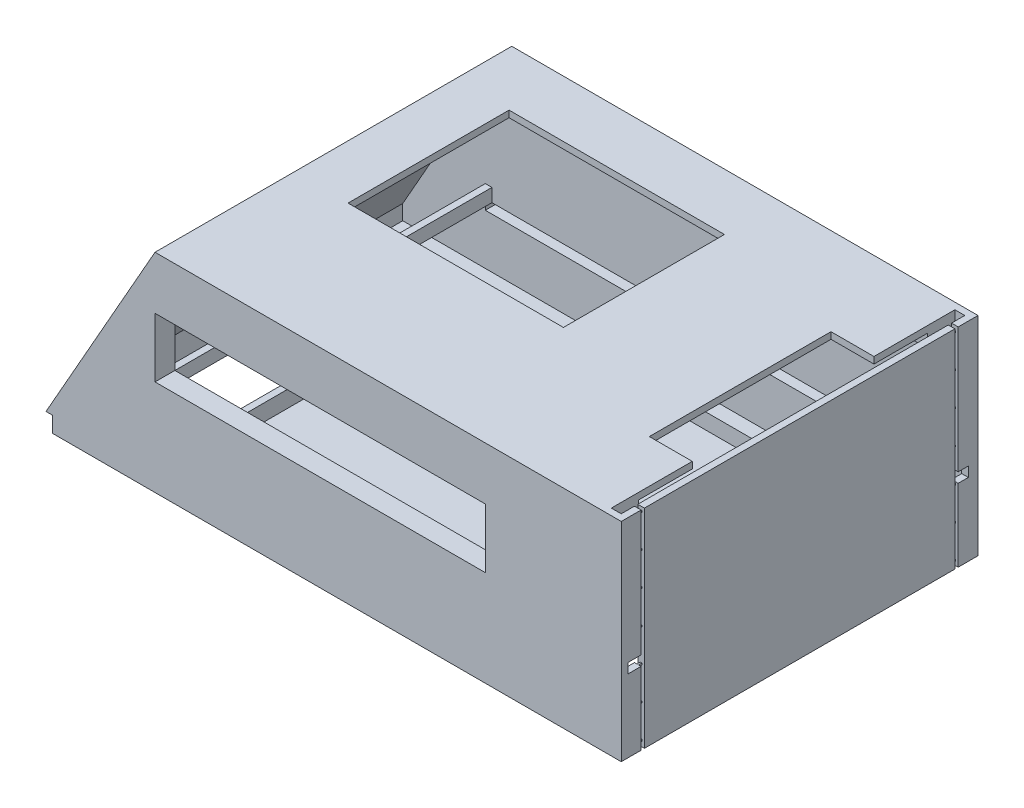
SolidWorks part; units mm, degrees
ref_plane "정면" through (0, 0, 0) normal (0, 0, 1) x (1, 0, 0)
ref_plane "윗면" through (0, 0, 0) normal (0, 1, 0) x (1, 0, 0)
ref_plane "우측면" through (0, 0, 0) normal (1, 0, 0) x (0, 0, -1)
sketch "스케치1" plane through (0, 0, 0) normal (0, 1, 0) x (1, 0, 0)
  line L1 (-87.075, 54) -> (87.075, 54)
  line L2 (-87.075, 54) -> (-87.075, -54)
  line L3 (-87.075, -54) -> (87.075, -54)
  line L4 (87.075, 54) -> (87.075, -54)
  line L5 (-87.075, 54) -> (87.075, -54) construction
  line L6 (-87.075, -54) -> (87.075, 54) construction
  point P0 (0, 0)
  dimension "D1" = 174.15
  dimension "D2" = 108
extrude "보스-돌출1" add sketch "스케치1" along normal blind 63
sketch "스케치4" plane through (87.075, 0, 0) normal (1, 0, 0) x (0, 0, -1)
  line L0 (-50, 0) -> (-50, 3)
  line L1 (-54, 0) -> (54, 0) construction
  line L2 (-50, 3) -> (-52, 3)
  line L3 (-52, 3) -> (-52, 4.5)
  line L4 (-52, 4.5) -> (-46, 4.5)
  line L5 (-46, 4.5) -> (-46, 3)
  line L6 (-46, 3) -> (-48, 3)
  line L7 (-48, 3) -> (-48, 0)
  line L8 (-48, 0) -> (-50, 0)
  line L10 (-54, 63) -> (-54, 0) construction
  line L11 (-50.25, 0) -> (-50.25, 2.75)
  line L12 (-50.25, 2.75) -> (-52.25, 2.75)
  line L13 (-52.25, 2.75) -> (-52.25, 4.75)
  line L14 (-52.25, 4.75) -> (-45.75, 4.75)
  line L15 (-45.75, 4.75) -> (-45.75, 2.75)
  line L16 (-45.75, 2.75) -> (-47.75, 2.75)
  line L17 (-47.75, 2.75) -> (-47.75, 0)
  line L18 (-50, 0) -> (-50.25, 0)
  line L19 (-48, 0) -> (-47.75, 0)
  dimension "D1" = 3
  dimension "D2" = 2
  dimension "D3" = 2
  dimension "D4" = 6
  dimension "D5" = 2
  dimension "D6" = 1.5
  dimension "D7" = 1.5
  dimension "D8" = 0.25
sketch "스케치5" plane through (-87.075, 0, 0) normal (-1, 0, 0) x (0, 0, 1)
  line L0 (50, 0) -> (50, 3) construction
  line L1 (50, 3) -> (52, 3) construction
  line L2 (52, 3) -> (52, 4.5) construction
  line L3 (52, 4.5) -> (46, 4.5) construction
  line L4 (46, 4.5) -> (46, 3) construction
  line L5 (46, 3) -> (48, 3) construction
  line L6 (48, 3) -> (48, 0) construction
  line L7 (48, 0) -> (50, 0) construction
  line L8 (50, 0) -> (50.25, 0) construction
  line L9 (50.25, 0) -> (50.25, 2.75) construction
  line L10 (50.25, 2.75) -> (52.25, 2.75) construction
  line L11 (52.25, 2.75) -> (52.25, 4.75) construction
  line L12 (52.25, 4.75) -> (45.75, 4.75) construction
  line L13 (45.75, 4.75) -> (45.75, 2.75) construction
  line L14 (45.75, 2.75) -> (47.75, 2.75) construction
  line L15 (47.75, 2.75) -> (47.75, 0) construction
  line L16 (48, 0) -> (47.75, 0) construction
  line L17 (50, 0) -> (50, 3)
  line L18 (50, 3) -> (52, 3)
  line L19 (52, 3) -> (52, 4.5)
  line L20 (52, 4.5) -> (46, 4.5)
  line L21 (46, 4.5) -> (46, 3)
  line L22 (46, 3) -> (48, 3)
  line L23 (48, 3) -> (48, 0)
  line L24 (48, 0) -> (50, 0)
  line L25 (50, 0) -> (50.25, 0)
  line L26 (50.25, 0) -> (50.25, 2.75)
  line L27 (50.25, 2.75) -> (52.25, 2.75)
  line L28 (52.25, 2.75) -> (52.25, 4.75)
  line L29 (52.25, 4.75) -> (45.75, 4.75)
  line L30 (45.75, 4.75) -> (45.75, 2.75)
  line L31 (45.75, 2.75) -> (47.75, 2.75)
  line L32 (47.75, 2.75) -> (47.75, 0)
  line L33 (48, 0) -> (47.75, 0)
  line L34 (0, 0) -> (0, 63) construction
  line L35 (-54, 63) -> (54, 63) construction
  line L36 (-48, 0) -> (-47.75, 0)
  line L37 (-47.75, 2.75) -> (-47.75, 0)
  line L38 (-45.75, 2.75) -> (-47.75, 2.75)
  line L39 (-45.75, 4.75) -> (-45.75, 2.75)
  line L40 (-52.25, 4.75) -> (-45.75, 4.75)
  line L41 (-52.25, 2.75) -> (-52.25, 4.75)
  line L42 (-50.25, 2.75) -> (-52.25, 2.75)
  line L43 (-50.25, 0) -> (-50.25, 2.75)
  line L44 (-50, 0) -> (-50.25, 0)
  line L45 (-48, 0) -> (-50, 0)
  line L46 (-48, 3) -> (-48, 0)
  line L47 (-46, 3) -> (-48, 3)
  line L48 (-46, 4.5) -> (-46, 3)
  line L49 (-52, 4.5) -> (-46, 4.5)
  line L50 (-52, 3) -> (-52, 4.5)
  line L51 (-50, 3) -> (-52, 3)
  line L52 (-50, 0) -> (-50, 3)
  line M2 (-54, 0) -> (54, 0)
extrude "컷-돌출2" cut sketch "스케치5" against normal up to surface (174.15 mm away) contours L52 L51 L50 L49 L48 L47 L46 L37 L38 L39 L40 L41 L42 L43 M2 | L52 L46 L47 L48 L49 L50 L51 M2 | L31 L32 L23 L22 L21 L20 L19 L18 L17 L26 L27 L28 L29 L30 M2 | L22 L23 L17 L18 L19 L20 L21 M2 up to face at (87.075, 31.5, 0)
sketch "스케치6" plane through (0, 0, 0) normal (0, -1, 0) x (1, 0, 0)
  line L0 (87.075, -54) -> (-87.075, -54) construction
  line L1 (-87.075, 54) -> (-85.075, 54)
  line L2 (-87.075, 54) -> (-87.075, -54)
  line L3 (-87.075, -54) -> (-85.075, -54)
  line L4 (-85.075, 54) -> (-85.075, -54)
  dimension "D1" = 2
extrude "컷-돌출3" cut sketch "스케치6" against normal up to surface (4.75 mm away) up to face at (0, 4.75, 49)
sketch "스케치7" plane through (87.075, 0, 0) normal (1, 0, 0) x (0, 0, -1)
  line L0 (-54, 63) -> (-54, 0) construction
  line L1 (-48, 57) -> (48, 57)
  line L2 (-48, 57) -> (-48, 6.75)
  line L3 (-48, 6.75) -> (48, 6.75)
  line L4 (48, 57) -> (48, 6.75)
  line L5 (54, 63) -> (54, 0) construction
  line L6 (45.75, 4.75) -> (52.25, 4.75) construction
  line L7 (-54, 63) -> (54, 63) construction
  dimension "D1" = 6
  dimension "D2" = 6
  dimension "D3" = 2
  dimension "D4" = 6
extrude "컷-돌출5" cut sketch "스케치7" against normal blind 168.15
sketch "스케치8" plane through (87.075, 0, 0) normal (1, 0, 0) x (0, 0, -1)
  line L0 (-48, 6.75) -> (48, 6.75) construction
  line L1 (-43.75, 6.75) -> (43.75, 6.75)
  line L2 (-43.75, 6.75) -> (-43.75, 2)
  line L3 (-43.75, 2) -> (43.75, 2)
  line L4 (43.75, 6.75) -> (43.75, 2)
  line L5 (-45.75, 2.75) -> (-45.75, 4.75) construction
  line L6 (-47.75, 0) -> (47.75, 0) construction
  line L7 (45.75, 2.75) -> (45.75, 4.75) construction
  dimension "D1" = 2
  dimension "D2" = 2
  dimension "D3" = 2
extrude "컷-돌출6" cut sketch "스케치8" against normal blind 168.15
sketch "스케치10" plane through (0, 2, 0) normal (0, 1, 0) x (1, 0, 0)
  line L4 (87.075, -43.75) -> (87.075, 43.75)
  line L5 (87.075, 43.75) -> (-81.075, 43.75)
  line L6 (-81.075, 43.75) -> (-81.075, -43.75)
  line L7 (-81.075, -43.75) -> (87.075, -43.75)
  line L8 (87.075, -43.75) -> (87.075, 43.75)
  line L9 (87.075, 43.75) -> (-81.075, 43.75)
  line L10 (-81.075, 43.75) -> (-81.075, -43.75)
  line L11 (-81.075, -43.75) -> (87.075, -43.75)
  dimension "D1" = 0
extrude "컷-돌출8" cut sketch "스케치10" along normal blind 59
ref_plane "평면1" through (0, 24, 0) normal (0, -1, 0) x (-1, 0, 0)
sketch "스케치12" plane through (0, 24, 0) normal (0, -1, 0) x (-1, 0, 0)
  line L1 (-87.075, 48) -> (81.075, 48)
  line L2 (-87.075, 48) -> (-87.075, -48)
  line L3 (-87.075, -48) -> (81.075, -48)
  line L4 (81.075, 48) -> (81.075, -48)
extrude "보스-돌출2" add sketch "스케치12" along normal blind 2
sketch "스케치15" plane through (0, 2, 0) normal (0, 1, 0) x (1, 0, 0)
  line L0 (-81.075, -43.75) -> (87.075, -43.75) construction
  line L1 (-81.075, 43.75) -> (-56.075, 43.75)
  line L2 (-81.075, 43.75) -> (-81.075, -26.25)
  line L3 (-81.075, -26.25) -> (-56.075, -26.25)
  line L4 (-56.075, 43.75) -> (-56.075, -26.25)
  line L5 (-36.7332, -43.75) -> (18.2668, -43.75)
  line L6 (-36.7332, -43.75) -> (-36.7332, -23.75)
  line L7 (-36.7332, -23.75) -> (18.2668, -23.75)
  line L8 (18.2668, -43.75) -> (18.2668, -23.75)
  line L9 (-81.075, 43.75) -> (87.075, 43.75) construction
  line L10 (42.6769, 43.75) -> (87.075, 43.75)
  line L11 (42.6769, 43.75) -> (42.6769, -43.75)
  line L12 (42.6769, -43.75) -> (87.075, -43.75)
  line L13 (87.075, 43.75) -> (87.075, -43.75)
  dimension "D1" = 25
  dimension "D2" = 70
  dimension "D3" = 20
  dimension "D4" = 55
extrude "컷-돌출9" cut sketch "스케치15" against normal blind 2
sketch "스케치16" plane through (0, 24, 0) normal (0, 1, 0) x (1, 0, 0)
  line L0 (87.075, -48) -> (-81.075, -48) construction
  line L1 (-81.075, 48) -> (-56.075, 48)
  line L2 (-81.075, 48) -> (-81.075, -48)
  line L3 (-81.075, -48) -> (-56.075, -48)
  line L4 (-56.075, 48) -> (-56.075, -48)
  line L5 (-81.075, 48) -> (87.075, 48) construction
  line L6 (54.7915, 48) -> (87.075, 48)
  line L7 (54.7915, 48) -> (54.7915, -48)
  line L8 (54.7915, -48) -> (87.075, -48)
  line L9 (87.075, 48) -> (87.075, -48)
  dimension "D1" = 25
extrude "컷-돌출10" cut sketch "스케치16" against normal blind 2
sketch "스케치17" plane through (0, 24, 0) normal (0, 1, 0) x (1, 0, 0)
  line L0 (54.7915, -48) -> (-56.075, -48) construction
  line L1 (-56.075, 48) -> (-54.075, 48)
  line L2 (-56.075, 48) -> (-56.075, -48)
  line L3 (-56.075, -48) -> (-54.075, -48)
  line L4 (-54.075, 48) -> (-54.075, -48)
  dimension "D1" = 2
extrude "보스-돌출3" add sketch "스케치17" along normal blind 5
sketch "스케치18" plane through (0, 2, 0) normal (0, 1, 0) x (1, 0, 0)
  line L0 (-81.075, -43.75) -> (87.075, -43.75) construction
  line L1 (-56.075, 43.75) -> (-54.075, 43.75)
  line L2 (-56.075, 43.75) -> (-56.075, -43.75)
  line L3 (-56.075, -43.75) -> (-54.075, -43.75)
  line L4 (-54.075, 43.75) -> (-54.075, -43.75)
  dimension "D1" = 2
extrude "보스-돌출4" add sketch "스케치18" along normal blind 5
sketch "스케치19" plane through (0, 0, 48) normal (0, 0, -1) x (-1, 0, 0)
  line L0 (54.075, 29) -> (54.075, 24) construction
  line L1 (54.075, 29) -> (-45.925, 29)
  line L2 (54.075, 29) -> (54.075, 47)
  line L3 (54.075, 47) -> (-45.925, 47)
  line L4 (-45.925, 29) -> (-45.925, 47)
  line L5 (-54.7915, 24) -> (54.075, 24) construction
  dimension "D1" = 5
  dimension "D2" = 100
  dimension "D3" = 18
extrude "컷-돌출11" cut sketch "스케치19" against normal blind 6
sketch "스케치20" plane through (0, 0, 54) normal (0, 0, 1) x (1, 0, 0)
  line L0 (-87.075, 4.75) -> (-54.075, 63)
  line L1 (-87.075, 63) -> (87.075, 63) construction
  line L2 (-54.075, 63) -> (-87.075, 63)
  line L3 (-87.075, 63) -> (-87.075, 4.75)
extrude "컷-돌출12" cut sketch "스케치20" against normal up to surface (108 mm away) up to face at (-28.3583, 22.5833, -54)
sketch "스케치21" plane through (0, 0, 54) normal (0, 0, 1) x (1, 0, 0)
  line L0 (-87.075, 4.75) -> (-84.7763, 4.75)
  line L1 (-87.075, 4.75) -> (-54.075, 63)
  line L2 (-84.7763, 4.75) -> (-51.7763, 63)
  line L3 (-54.075, 63) -> (-51.7763, 63)
  line L4 (-54.075, 63) -> (87.075, 63) construction
  dimension "D1" = 2
extrude "보스-돌출5" add sketch "스케치21" against normal up to surface (108 mm away) up to face at (-22.8583, 22.5833, -54)
sketch "스케치23" plane through (0, 63, 0) normal (0, 1, 0) x (1, 0, 0)
  line L5 (-37.7431, 36.8539) -> (27.4625, 36.8539)
  line L6 (-37.7431, 36.8539) -> (-37.7431, -11.8908)
  line L7 (-37.7431, -11.8908) -> (27.4625, -11.8908)
  line L8 (27.4625, 36.8539) -> (27.4625, -11.8908)
extrude "컷-돌출13" cut sketch "스케치23" against normal blind 2
sketch "스케치26" plane through (0, 63, 0) normal (0, 1, 0) x (1, 0, 0)
  line L0 (87.075, 54) -> (-54.075, 54) construction
  line L1 (82.075, 52) -> (85.075, 52)
  line L2 (82.075, 52) -> (82.075, -52)
  line L3 (82.075, -52) -> (85.075, -52)
  line L4 (85.075, 52) -> (85.075, 48)
  line L5 (-54.075, -54) -> (87.075, -54) construction
  line L6 (87.075, -54) -> (87.075, 54) construction
  line L7 (85.075, -48) -> (85.075, -52)
  line L8 (87.075, 48) -> (85.075, 48)
  line L9 (87.075, 48) -> (87.075, -48)
  line L10 (87.075, -48) -> (85.075, -48)
  point P6 (83.575, -52)
  dimension "D1" = 3
  dimension "D2" = 2
  dimension "D3" = 2
  dimension "D4" = 2
  dimension "D5" = 6
  dimension "D6" = 6
extrude "컷-돌출14" cut sketch "스케치26" against normal up to surface (63 mm away)
sketch "스케치28" plane through (0, 4.75, 0) normal (0, -1, 0) x (1, 0, 0)
  line L0 (87.075, 52.25) -> (-85.075, 52.25) construction
  line L1 (87.075, 48) -> (85.075, 48)
  line L2 (87.075, 48) -> (87.075, 52.25)
  line L3 (87.075, 52.25) -> (85.075, 52.25)
  line L4 (85.075, 48) -> (85.075, 52.25)
  line L5 (87.075, -52.25) -> (-85.075, -52.25) construction
  line L6 (87.075, -48) -> (85.075, -48)
  line L7 (87.075, -48) -> (87.075, -52.25)
  line L8 (87.075, -52.25) -> (85.075, -52.25)
  line L9 (85.075, -48) -> (85.075, -52.25)
extrude "보스-돌출6" add sketch "스케치28" along normal up to surface (4.75 mm away) up to face at (42.2875, 0, 51.625)
sketch "스케치29" plane through (0, 63, 0) normal (0, 1, 0) x (1, 0, 0)
  line L0 (82.325, 51.5) -> (84.825, 51.5)
  line L1 (82.325, 51.5) -> (82.325, -51.5)
  line L2 (82.325, -51.5) -> (84.825, -51.5)
  line L3 (84.825, 51.5) -> (84.825, -51.5)
  line L4 (84.825, 47.5) -> (86.825, 47.5)
  line L5 (84.825, 47.5) -> (84.825, -47.5)
  line L6 (84.825, -47.5) -> (86.825, -47.5)
  line L7 (86.825, 47.5) -> (86.825, -47.5)
  line L8 (85.075, 52) -> (82.075, 52) construction
  line L9 (82.075, 52) -> (82.075, -52) construction
  dimension "D1" = 2.5
  dimension "D2" = 4
  dimension "D3" = 0.5
  dimension "D4" = 0.25
sketch "스케치31" plane through (0, 63, 0) normal (0, 1, 0) x (1, 0, 0)
  line L1 (69.075, 27.5) -> (82.075, 27.5)
  line L2 (69.075, 27.5) -> (69.075, -27.5)
  line L3 (69.075, -27.5) -> (82.075, -27.5)
  line L4 (82.075, 27.5) -> (82.075, -27.5)
  line L5 (87.075, 54) -> (-54.075, 54) construction
  line L6 (82.075, 52) -> (82.075, -52) construction
  dimension "D1" = 13
  dimension "D2" = 55
  dimension "D3" = 26.5
extrude "컷-돌출15" cut sketch "스케치31" against normal blind 10
sketch "스케치34" plane through (87.075, 0, 0) normal (1, 0, 0) x (0, 0, -1)
  line L0 (-54, 63) -> (-54, 0) construction
  line L1 (-52, 22) -> (51.0709, 22)
  line L2 (-52, 22) -> (-52, 25)
  line L3 (-52, 25) -> (51.0709, 25)
  line L4 (51.0709, 22) -> (51.0709, 25)
  dimension "D1" = 2
  dimension "D2" = 3
extrude "컷-돌출16" cut sketch "스케치34" against normal blind 143.15 contours L3 L4 L1 L2
sketch "스케치36" plane through (87.075, 0, 0) normal (1, 0, 0) x (0, 0, -1)
  line L0 (-52, 23.5) -> (51.0709, 23.5)
  line L1 (-52, 22) -> (-52, 25) construction
  line L2 (51.0709, 22) -> (51.0709, 25) construction
  dimension "D1" = 103.0709
sketch "스케치37" plane through (0, 0, 48) normal (0, 0, -1) x (-1, 0, 0)
  line L0 (-86.325, 52.0093) -> (-85.825, 52.0093)
  line L1 (-86.325, 62.0093) -> (-85.825, 62.0093)
  line L2 (-86.325, 62.0093) -> (-86.325, 61.5093)
  line L3 (-86.325, 61.5093) -> (-85.825, 61.5093)
  line L4 (-85.825, 62.0093) -> (-85.825, 61.5093)
  line L5 (-86.325, 52.0093) -> (-86.325, 51.5093)
  line L6 (-87.075, 63) -> (-87.075, 25) construction
  line L7 (-85.825, 52.0093) -> (-85.825, 51.5093)
  line L8 (-86.325, 51.5093) -> (-85.825, 51.5093)
  line L9 (-86.325, 42.0093) -> (-85.825, 42.0093)
  line L10 (-86.325, 42.0093) -> (-86.325, 41.5093)
  line L11 (-85.825, 42.0093) -> (-85.825, 41.5093)
  line L12 (-86.325, 41.5093) -> (-85.825, 41.5093)
  line L13 (-86.325, 32.0093) -> (-85.825, 32.0093)
  line L14 (-86.325, 32.0093) -> (-86.325, 31.5093)
  line L15 (-85.825, 32.0093) -> (-85.825, 31.5093)
  line L16 (-86.325, 31.5093) -> (-85.825, 31.5093)
  line L17 (-86.325, 22.0093) -> (-85.825, 22.0093)
  line L18 (-86.325, 22.0093) -> (-86.325, 21.5093)
  line L19 (-85.825, 22.0093) -> (-85.825, 21.5093)
  line L20 (-86.325, 21.5093) -> (-85.825, 21.5093)
  line L21 (-86.325, 12.0093) -> (-85.825, 12.0093)
  line L22 (-86.325, 12.0093) -> (-86.325, 11.5093)
  line L23 (-85.825, 12.0093) -> (-85.825, 11.5093)
  line L24 (-86.325, 11.5093) -> (-85.825, 11.5093)
  line L25 (-86.325, 2.0093) -> (-85.825, 2.0093)
  line L26 (-86.325, 2.0093) -> (-86.325, 1.5093)
  line L27 (-85.825, 2.0093) -> (-85.825, 1.5093)
  line L28 (-86.325, 1.5093) -> (-85.825, 1.5093)
  dimension "D1" = 0.5
  dimension "D2" = 0.5
  dimension "D3" = 0.75
  dimension "D4" = 7
extrude "보스-돌출7" add sketch "스케치37" along normal blind 1 separate body
sketch "스케치40" plane through (0, 0, -48) normal (0, 0, 1) x (1, 0, 0)
  line L0 (87.075, 25) -> (87.075, 63) construction
  line L1 (85.825, 61.6463) -> (86.325, 61.6463)
  line L2 (85.825, 61.6463) -> (85.825, 61.1463)
  line L3 (85.825, 61.1463) -> (86.325, 61.1463)
  line L4 (86.325, 61.6463) -> (86.325, 61.1463)
  line L5 (85.825, 51.6463) -> (85.825, 51.1463)
  line L6 (85.825, 51.6463) -> (86.325, 51.6463)
  line L7 (86.325, 51.6463) -> (86.325, 51.1463)
  line L8 (85.825, 51.1463) -> (86.325, 51.1463)
  line L9 (85.825, 41.6463) -> (85.825, 41.1463)
  line L10 (85.825, 41.6463) -> (86.325, 41.6463)
  line L11 (86.325, 41.6463) -> (86.325, 41.1463)
  line L12 (85.825, 41.1463) -> (86.325, 41.1463)
  line L13 (85.825, 31.6463) -> (85.825, 31.1463)
  line L14 (85.825, 31.6463) -> (86.325, 31.6463)
  line L15 (86.325, 31.6463) -> (86.325, 31.1463)
  line L16 (85.825, 31.1463) -> (86.325, 31.1463)
  line L17 (85.825, 21.6463) -> (85.825, 21.1463)
  line L18 (85.825, 21.6463) -> (86.325, 21.6463)
  line L19 (86.325, 21.6463) -> (86.325, 21.1463)
  line L20 (85.825, 21.1463) -> (86.325, 21.1463)
  line L21 (85.825, 11.6463) -> (85.825, 11.1463)
  line L22 (85.825, 11.6463) -> (86.325, 11.6463)
  line L23 (86.325, 11.6463) -> (86.325, 11.1463)
  line L24 (85.825, 11.1463) -> (86.325, 11.1463)
  line L25 (85.825, 1.6463) -> (85.825, 1.1463)
  line L26 (85.825, 1.6463) -> (86.325, 1.6463)
  line L27 (86.325, 1.6463) -> (86.325, 1.1463)
  line L28 (85.825, 1.1463) -> (86.325, 1.1463)
  dimension "D1" = 0.5
  dimension "D2" = 0.5
  dimension "D3" = 0.75
  dimension "D4" = 7
extrude "보스-돌출8" add sketch "스케치40" along normal blind 1
sketch "스케치42" plane through (0, 63, 0) normal (0, 1, 0) x (1, 0, 0)
  line L1 (85.075, 47) -> (87.0776, 47)
  line L2 (85.075, 47) -> (85.075, -47)
  line L3 (85.075, -47) -> (87.0776, -47)
  line L4 (87.0776, 47) -> (87.0776, -47)
extrude "보스-돌출9" add sketch "스케치42" against normal up to surface (63 mm away) up to face at (42.2875, 0, 51.0625)
